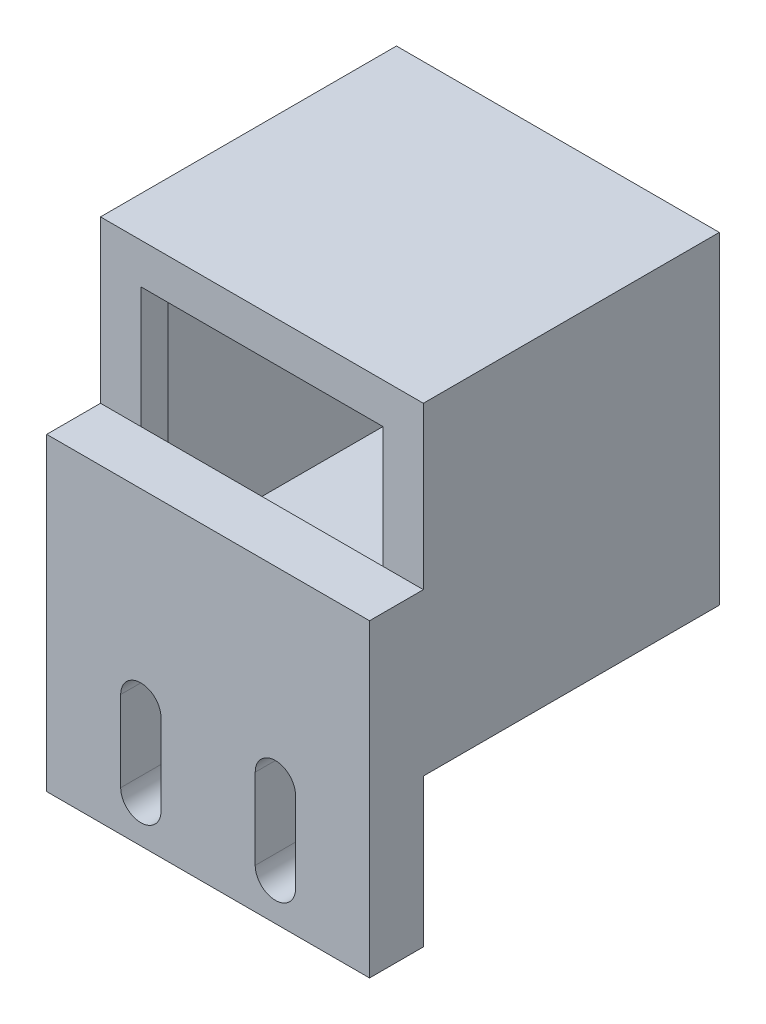
SolidWorks part; units mm, degrees
ref_plane "前视基准面" through (0, 0, 0) normal (0, 0, 1) x (1, 0, 0)
ref_plane "上视基准面" through (0, 0, 0) normal (0, 1, 0) x (1, 0, 0)
ref_plane "右视基准面" through (0, 0, 0) normal (1, 0, 0) x (0, 0, -1)
sketch "草图1" plane through (0, 0, 0) normal (0, 0, 1) x (1, 0, 0)
  line L1 (-12, 12) -> (12, 12)
  line L2 (-12, 12) -> (-12, -12)
  line L3 (-12, -12) -> (12, -12)
  line L4 (12, 12) -> (12, -12)
  line L5 (-12, 12) -> (12, -12) construction
  line L6 (-12, -12) -> (12, 12) construction
  point P0 (0, 0)
  dimension "D1" = 24
extrude "凸台-拉伸2" add sketch "草图1" along normal blind 20
sketch "草图3" plane through (0, 0, 20) normal (0, 0, 1) x (1, 0, 0)
  line L1 (-10.5, 10.5) -> (10.5, 10.5)
  line L2 (-10.5, 10.5) -> (-10.5, -10.5)
  line L3 (-10.5, -10.5) -> (10.5, -10.5)
  line L4 (10.5, 10.5) -> (10.5, -10.5)
  line L5 (-10.5, 10.5) -> (10.5, -10.5) construction
  line L6 (-10.5, -10.5) -> (10.5, 10.5) construction
  point P0 (0, 0)
  dimension "D1" = 21
extrude "切除-拉伸1" cut sketch "草图3" against normal blind 20
sketch "草图4" plane through (0, 0, 20) normal (0, 0, 1) x (1, 0, 0)
  line L0 (12, -12) -> (12, 12) construction
  line L1 (-12, 12) -> (12, 12)
  line L2 (-12, 12) -> (-12, 9)
  line L3 (-12, 9) -> (12, 9)
  line L4 (12, 12) -> (12, 9)
  dimension "D1" = 3
extrude "凸台-拉伸8" add sketch "草图4" along normal blind 2
sketch "草图8" plane through (0, 0, 20) normal (0, 0, 1) x (1, 0, 0)
  line L0 (-12, 9) -> (12, 9) construction
  line L1 (-12, -12) -> (-9, -12)
  line L2 (-12, -12) -> (-12, 9)
  line L3 (-12, 9) -> (-9, 9)
  line L4 (-9, -12) -> (-9, 9)
  dimension "D1" = 3
extrude "凸台-拉伸9" add sketch "草图8" along normal blind 2
sketch "草图9" plane through (0, 0, 20) normal (0, 0, 1) x (1, 0, 0)
  line L0 (12, -12) -> (12, 9) construction
  line L1 (-9, -12) -> (12, -12)
  line L2 (-9, -12) -> (-9, -9)
  line L3 (-9, -9) -> (12, -9)
  line L4 (12, -12) -> (12, -9)
  dimension "D1" = 3
extrude "凸台-拉伸10" add sketch "草图9" along normal blind 2
sketch "草图10" plane through (0, 0, 20) normal (0, 0, 1) x (1, 0, 0)
  line L0 (12, -9) -> (-9, -9) construction
  line L1 (12, 9) -> (9, 9)
  line L2 (12, 9) -> (12, -9)
  line L3 (12, -9) -> (9, -9)
  line L4 (9, 9) -> (9, -9)
  dimension "D1" = 3
extrude "凸台-拉伸11" add sketch "草图10" along normal blind 2
sketch "草图11" plane through (0, 0, 22) normal (0, 0, 1) x (1, 0, 0)
  line L0 (-12, 12) -> (-12, -12) construction
  line L1 (-12, 0) -> (12, 0)
  line L2 (-12, 0) -> (-12, -23)
  line L3 (-12, -23) -> (12, -23)
  line L4 (12, 0) -> (12, -23)
  dimension "D1" = 23
extrude "凸台-拉伸12" add sketch "草图11" along normal blind 4
sketch "草图12" plane through (0, 0, 26) normal (0, 0, 1) x (1, 0, 0)
  line L0 (0, 3.4096) -> (0, -24.5641) construction
  line L1 (-5, -14) -> (-5, -20) construction
  line L2 (-3.5, -14) -> (-3.5, -20)
  line L3 (-6.5, -14) -> (-6.5, -20)
  line L4 (-12, -23) -> (12, -23) construction
  line L5 (5, -14) -> (5, -20) construction
  line L6 (3.5, -14) -> (3.5, -20)
  line L7 (6.5, -14) -> (6.5, -20)
  arc A0 (-3.5, -14) -> (-6.5, -14) centre (-5, -14) ccw
  arc A1 (-6.5, -20) -> (-3.5, -20) centre (-5, -20) ccw
  arc A2 (3.5, -14) -> (6.5, -14) centre (5, -14) cw
  arc A3 (6.5, -20) -> (3.5, -20) centre (5, -20) cw
  point P5 (-5, -17)
  point P14 (5, -17)
  dimension "D1" = 1.5
  dimension "D2" = 3
  dimension "D3" = 6
  dimension "D4" = 5
extrude "切除-拉伸2" cut sketch "草图12" against normal blind 4
